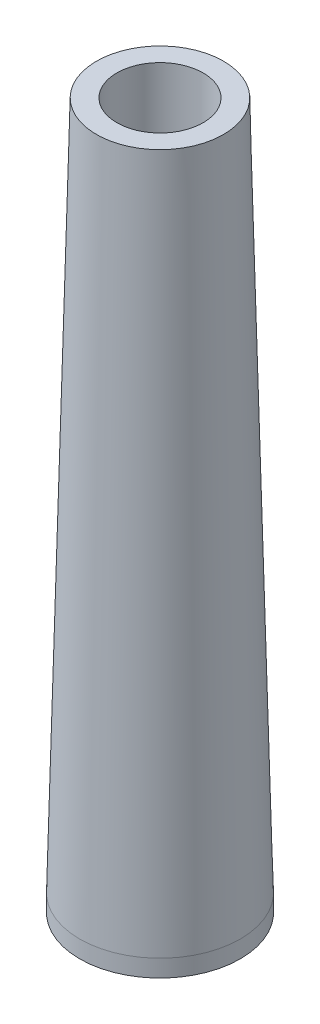
SolidWorks part; units mm, degrees
ref_plane "Alzado" through (0, 0, 0) normal (0, 0, 1) x (1, 0, 0)
ref_plane "Planta" through (0, 0, 0) normal (0, 1, 0) x (1, 0, 0)
ref_plane "Vista lateral" through (0, 0, 0) normal (1, 0, 0) x (0, 0, -1)
sketch "Croquis1" plane through (0, 0, 0) normal (0, 1, 0) x (1, 0, 0)
  circle A0 centre (0, 0) radius 14
  dimension "D1" = 28
extrude "Saliente-Extruir1" add sketch "Croquis1" along normal blind 3
sketch "Croquis2" plane through (0, 3, 0) normal (0, 1, 0) x (1, 0, 0)
  circle A0 centre (0, 0) radius 11.075
  dimension "D1" = 22.15
extrude "Saliente-Extruir2" add sketch "Croquis2" along normal blind 120
sketch "Croquis3" plane through (0, 123, 0) normal (0, 1, 0) x (1, 0, 0)
  circle A0 centre (0, 0) radius 7.525
  circle A1 centre (0, 0) radius 11.075 construction
  dimension "D1" = 3.55
extrude "Cortar-Extruir2" cut sketch "Croquis3" against normal through all
sketch "Croquis4" plane through (0, 0, 0) normal (0, 0, 1) x (1, 0, 0)
  line L0 (0, 0) -> (0, 125.2226) construction
  line L1 (14, 3) -> (11.075, 3)
  line L2 (11.075, 3) -> (11.075, 123)
  line L3 (11.075, 123) -> (14, 3)
revolve "Revolución1" add sketch "Croquis4" angle 360 about L0
